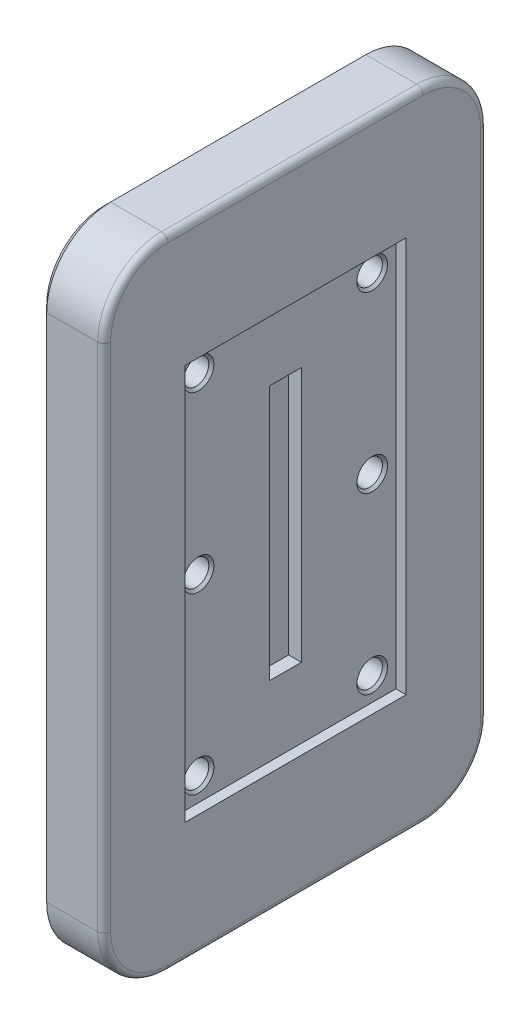
SolidWorks part; units mm, degrees
ref_plane "Front Plane" through (0, 0, 0) normal (0, 0, 1) x (1, 0, 0)
ref_plane "Top Plane" through (0, 0, 0) normal (0, 1, 0) x (1, 0, 0)
ref_plane "Right Plane" through (0, 0, 0) normal (1, 0, 0) x (0, 0, -1)
sketch "Sketch1" plane through (0, 0, 0) normal (1, 0, 0) x (0, 0, -1)
  line L1 (-30, -50) -> (30, -50)
  line L2 (-30, -50) -> (-30, 50)
  line L3 (-30, 50) -> (30, 50)
  line L4 (30, -50) -> (30, 50)
  line L5 (-30, -50) -> (30, 50) construction
  line L6 (-30, 50) -> (30, -50) construction
  point P0 (0, 0)
  dimension "D1" = 100
  dimension "D2" = 60
extrude "Boss-Extrude1" add sketch "Sketch1" along normal blind 10
sketch "Sketch2" plane through (10, 0, 0) normal (1, 0, 0) x (0, 0, -1)
  line L1 (-17.3, -31) -> (17.3, -31)
  line L2 (-17.3, -31) -> (-17.3, 31)
  line L3 (-17.3, 31) -> (17.3, 31)
  line L4 (17.3, -31) -> (17.3, 31)
  line L5 (-17.3, -31) -> (17.3, 31) construction
  line L6 (-17.3, 31) -> (17.3, -31) construction
  point P0 (0, 0)
  dimension "D1" = 62
  dimension "D2" = 34.6
extrude "Cut-Extrude1" cut sketch "Sketch2" against normal blind 1.6
sketch "Sketch3" plane through (8.4, 0, 0) normal (1, 0, 0) x (0, 0, -1)
  line L0 (-13.6, 27.3) -> (-13.6, -27.3) construction
  line L1 (-13.6, 0) -> (13.6, 0) construction
  circle A0 centre (-13.6, 27.3) radius 2
  circle A1 centre (13.6, 27.3) radius 2
  circle A2 centre (-13.6, 0) radius 2
  circle A3 centre (13.6, 0) radius 2
  circle A4 centre (-13.6, -27.3) radius 2
  circle A5 centre (13.6, -27.3) radius 2
  point P12 (0, 0)
  dimension "D1" = 4
  dimension "D2" = 54.6
  dimension "D3" = 27.2
extrude "Cut-Extrude2" cut sketch "Sketch3" against normal through all
fillet "Fillet1" radius 10 4 edges at (5, -50, 30) (5, 50, 30) (5, 50, -30) (5, -50, -30)
fillet "Fillet2" radius 1 8 edges at (10, 0, 30) (10, 47.0711, 27.0711) (10, 50, 0) (10, 47.0711, -27.0711) (10, 0, -30) (10, -47.0711, -27.0711) (10, -50, 0) (10, -47.0711, 27.0711)
chamfer "Chamfer1" distance 1 angle 45 14 edges at (0, -47.0711, -27.0711) (0, 0, -30) (0, 47.0711, -27.0711) (0, 50, 0) (0, 47.0711, 27.0711) (0, 0, 30) (0, -47.0711, 27.0711) (0, -50, 0) (0, 27.3, 11.6) (0, -27.3, -15.6) (0, 27.3, -15.6) (0, 0, 11.6) (0, 0, -15.6) (0, -27.3, 11.6)
chamfer "Chamfer2" distance 0.4 angle 45 6 edges at (8.4, 27.3, 11.6) (8.4, 0, 11.6) (8.4, -27.3, 11.6) (8.4, -27.3, -15.6) (8.4, 0, -15.6) (8.4, 27.3, -15.6)
sketch "Sketch4" plane through (8.4, 0, 0) normal (1, 0, 0) x (0, 0, -1)
  line L1 (-2.5, -20) -> (2.5, -20)
  line L2 (-2.5, -20) -> (-2.5, 20)
  line L3 (-2.5, 20) -> (2.5, 20)
  line L4 (2.5, -20) -> (2.5, 20)
  line L5 (-2.5, -20) -> (2.5, 20) construction
  line L6 (-2.5, 20) -> (2.5, -20) construction
  point P0 (0, 0)
  dimension "D1" = 5
  dimension "D2" = 40
extrude "Cut-Extrude3" cut sketch "Sketch4" against normal blind 2
